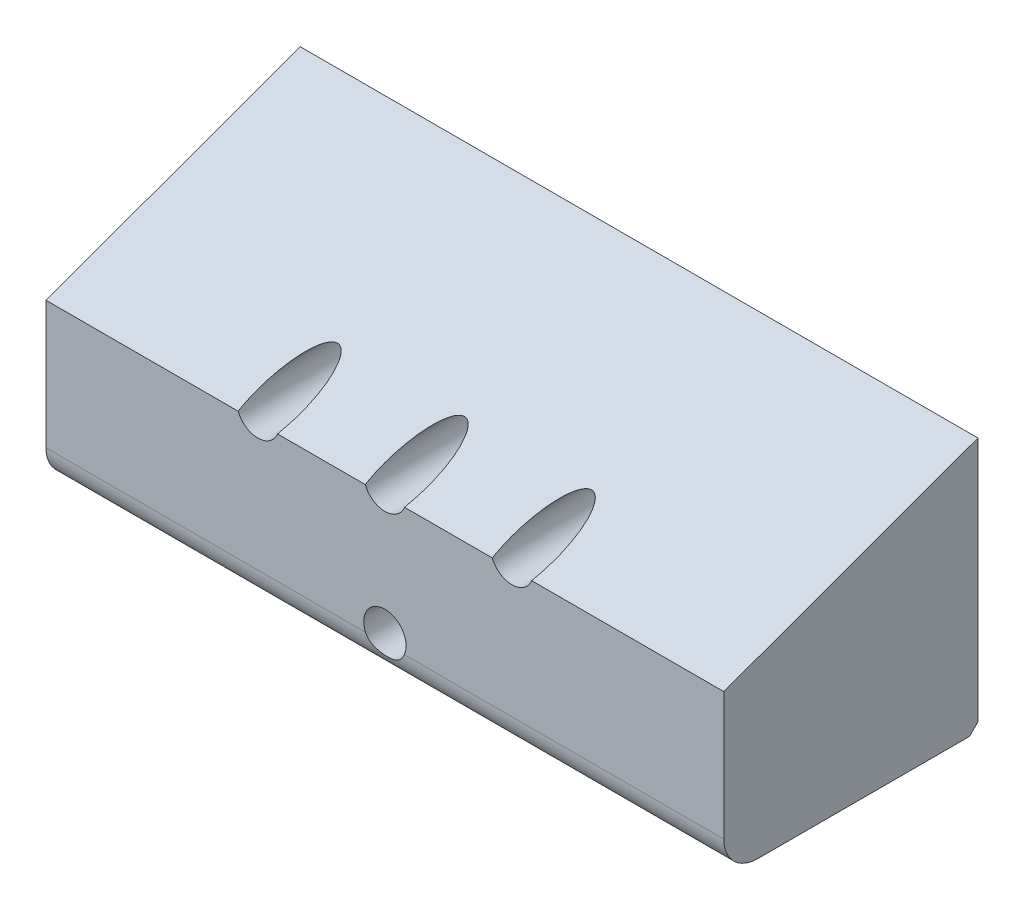
SolidWorks part; units mm, degrees
ref_plane "前视基准面" through (0, 0, 0) normal (0, 0, 1) x (1, 0, 0)
ref_plane "上视基准面" through (0, 0, 0) normal (0, 1, 0) x (1, 0, 0)
ref_plane "右视基准面" through (0, 0, 0) normal (1, 0, 0) x (0, 0, -1)
sketch "草图1" plane through (0, 0, 0) normal (1, 0, 0) x (0, 0, -1)
  line L0 (0, 0) -> (15, 5.4596)
  line L1 (15, 5.4596) -> (15, -9.5404)
  line L2 (15, -9.5404) -> (0, -9.5404)
  line L3 (0, -9.5404) -> (0, 0)
  dimension "D1" = 110
  dimension "D2" = 15
  dimension "D3" = 15
extrude "凸台-拉伸1" add sketch "草图1" against normal blind 40
fillet "圆角1" radius 2 1 edges at (-20, -9.5404, 0)
chamfer "倒角2" distance 0.5 angle 45 1 edges at (-20, -9.5404, -15)
sketch "草图2" plane through (0, 0, -15) normal (0, 0, -1) x (-1, 0, 0)
  line L0 (20, 5.4596) -> (20, -9.0404) construction
  line L1 (40, 5.4596) -> (0, 5.4596) construction
  line L2 (0, -9.0404) -> (40, -9.0404) construction
  circle A0 centre (20, 0.4596) radius 1.25
  circle A1 centre (27.5, 0.4596) radius 1.25
  circle A2 centre (12.5, 0.4596) radius 1.25
  circle A3 centre (20, -7.0404) radius 1.25
  dimension "D1" = 5
  dimension "D2" = 2.5
  dimension "D3" = 2.5
  dimension "D4" = 2.5
  dimension "D6" = 2.5
  dimension "D5" = 15
  dimension "D7" = 7.5
extrude "切除-拉伸1" cut sketch "草图2" against normal through all
